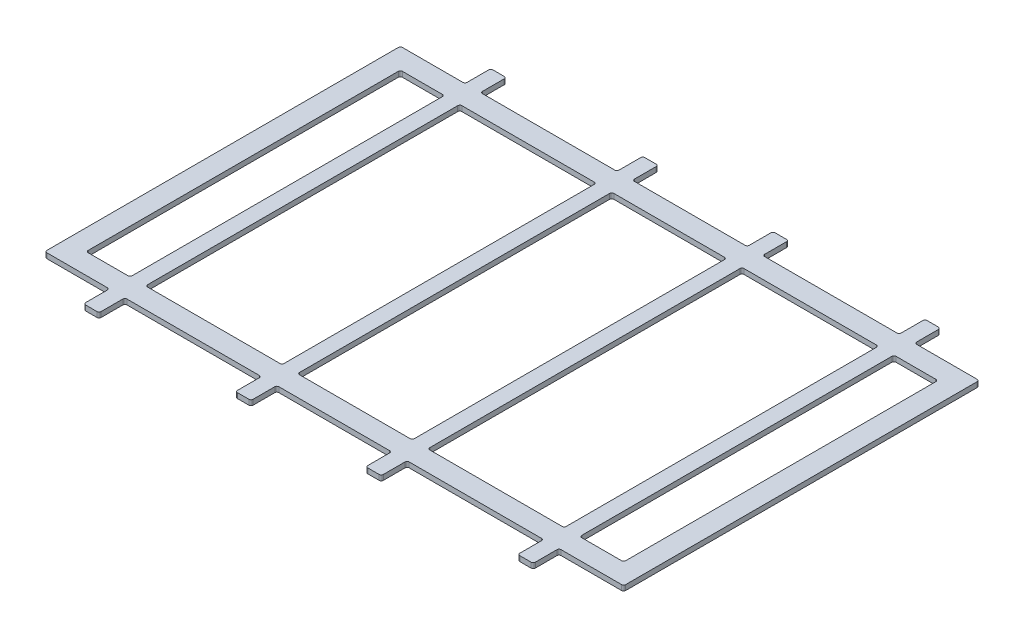
SolidWorks part; units mm, degrees
material "Plain Carbon Steel"
ref_plane "Front Plane" through (0, 0, 0) normal (0, 0, 1) x (1, 0, 0)
ref_plane "Top Plane" through (0, 0, 0) normal (0, 1, 0) x (1, 0, 0)
ref_plane "Right Plane" through (0, 0, 0) normal (1, 0, 0) x (0, 0, -1)
sketch "Sketch1" plane through (0, 0, 0) normal (0, 1, 0) x (1, 0, 0)
  line L1 (280, -172) -> (-280, -172)
  line L2 (280, -172) -> (280, 172)
  line L3 (280, 172) -> (-280, 172)
  line L4 (-280, -172) -> (-280, 172)
  line L5 (280, -172) -> (-280, 172) construction
  line L6 (280, 172) -> (-280, -172) construction
  point P0 (0, 0)
  dimension "D1" = 560
  dimension "D2" = 344
extrude "Boss-Extrude1" add sketch "Sketch1" along normal blind 5
sketch "Sketch2" plane through (0, 5, 0) normal (0, 1, 0) x (1, 0, 0)
  line L0 (-280, -172) -> (280, -172) construction
  line L1 (-70.5, -172) -> (-55.5, -172)
  line L2 (-70.5, -172) -> (-70.5, -197)
  line L3 (-70.5, -197) -> (-55.5, -197)
  line L4 (-55.5, -172) -> (-55.5, -197)
  line L5 (-210, -172) -> (-210, -197) construction
  line L6 (-202.5, -172) -> (-217.5, -172)
  line L7 (-202.5, -172) -> (-202.5, -197)
  line L8 (-202.5, -197) -> (-217.5, -197)
  line L9 (-217.5, -172) -> (-217.5, -197)
  line L10 (-63, -172) -> (-63, -197) construction
  dimension "D1" = 63
  dimension "D2" = 147
  dimension "D3" = 25
  dimension "D4" = 15
  dimension "D5" = 15
extrude "Boss-Extrude2" add sketch "Sketch2" against normal up to surface (5 mm away) up to face at (0, 0, 0)
mirror "Mirror4" about plane through (0, 0, 0) normal (1, 0, 0) of "Boss-Extrude2"
mirror "Mirror5" about plane through (0, 0, 0) normal (0, 0, 1) of "Mirror4", "Boss-Extrude2"
fillet "Fillet3" radius 2 36 edges at (-70.5, 2.5, -172) (-70.5, 2.5, -197) (-55.5, 2.5, -197) (-55.5, 2.5, -172) (55.5, 2.5, -172) (55.5, 2.5, -197) (70.5, 2.5, -197) (70.5, 2.5, -172) (202.5, 2.5, -172) (202.5, 2.5, -197) (217.5, 2.5, -197) (217.5, 2.5, -172) (280, 2.5, -172) (280, 2.5, 172) (217.5, 2.5, 172) (217.5, 2.5, 197) (202.5, 2.5, 197) (202.5, 2.5, 172) (70.5, 2.5, 172) (70.5, 2.5, 197) (55.5, 2.5, 197) (55.5, 2.5, 172) (-55.5, 2.5, 172) (-55.5, 2.5, 197) (-70.5, 2.5, 197) (-70.5, 2.5, 172) (-202.5, 2.5, 172) (-202.5, 2.5, 197) (-217.5, 2.5, 197) (-217.5, 2.5, 172) (-280, 2.5, 172) (-202.5, 2.5, -172) (-202.5, 2.5, -197) (-217.5, 2.5, -172) (-217.5, 2.5, -197) (-280, 2.5, -172)
sketch "Sketch3" plane through (0, 5, 0) normal (0, 1, 0) x (1, 0, 0)
  line L0 (217.5, -184.5) -> (217.5, 184.5) construction
  line L1 (217.5, -174) -> (217.5, -195) construction
  line L2 (217.5, 174) -> (217.5, 195) construction
  line L3 (202.5, 184.5) -> (202.5, -184.5) construction
  line L4 (202.5, 195) -> (202.5, 174) construction
  line L5 (202.5, -195) -> (202.5, -174) construction
  line L6 (70.5, -184.5) -> (70.5, 184.5) construction
  line L7 (70.5, -174) -> (70.5, -195) construction
  line L8 (70.5, 174) -> (70.5, 195) construction
  line L9 (55.5, 184.5) -> (55.5, -184.5) construction
  line L10 (55.5, 195) -> (55.5, 174) construction
  line L11 (55.5, -195) -> (55.5, -174) construction
  line L12 (217.5, -152) -> (260, -152)
  line L13 (260, -152) -> (260, 152)
  line L14 (260, 152) -> (217.5, 152)
  line L15 (217.5, -152) -> (217.5, 152)
  line L16 (219.5, -172) -> (278, -172) construction
  line L17 (280, -170) -> (280, 170) construction
  line L18 (278, 172) -> (219.5, 172) construction
  line L20 (202.5, 152) -> (70.5, 152)
  line L21 (202.5, 152) -> (202.5, -152)
  line L22 (202.5, -152) -> (70.5, -152)
  line L23 (70.5, 152) -> (70.5, -152)
  line L24 (55.5, -152) -> (0, -152)
  line L25 (55.5, -152) -> (55.5, 152)
  line L26 (55.5, 152) -> (0, 152)
  line L27 (0, -152) -> (0, 152)
  dimension "D1" = 20
  dimension "D2" = 20
  dimension "D3" = 20
extrude "Cut-Extrude1" cut sketch "Sketch3" against normal through all
mirror "Mirror6" about plane through (0, 0, 0) normal (1, 0, 0) of "Cut-Extrude1"
fillet "Fillet4" radius 2 20 edges at (-260, 2.5, 152) (-260, 2.5, -152) (-217.5, 2.5, -152) (55.5, 2.5, -152) (55.5, 2.5, 152) (-55.5, 2.5, 152) (-55.5, 2.5, -152) (260, 2.5, -152) (260, 2.5, 152) (217.5, 2.5, 152) (217.5, 2.5, -152) (70.5, 2.5, 152) (70.5, 2.5, -152) (202.5, 2.5, -152) (202.5, 2.5, 152) (-202.5, 2.5, -152) (-70.5, 2.5, -152) (-202.5, 2.5, 152) (-70.5, 2.5, 152) (-217.5, 2.5, 152)
